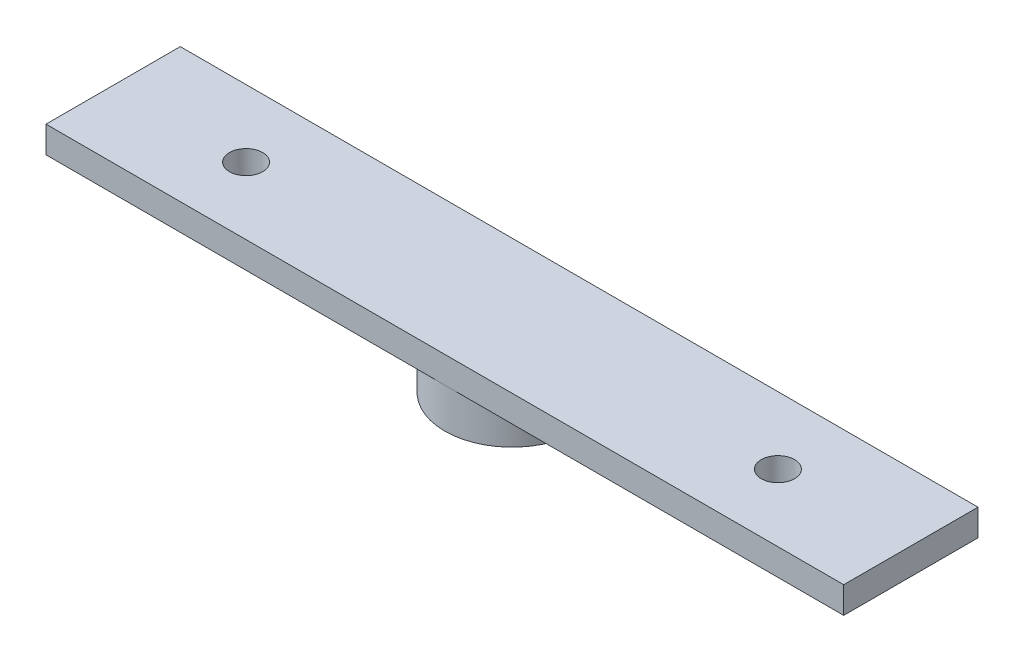
SolidWorks part; units mm, degrees
ref_plane "Front Plane" through (0, 0, 0) normal (0, 0, 1) x (1, 0, 0)
ref_plane "Top Plane" through (0, 0, 0) normal (0, 1, 0) x (1, 0, 0)
ref_plane "Right Plane" through (0, 0, 0) normal (1, 0, 0) x (0, 0, -1)
ref_axis "Axis1" through (0, 97.0223, 0) along (0, -1, 0)
sketch "Sketch1" plane through (0, 0, 0) normal (0, 0, 1) x (1, 0, 0)
  line L0 (3.05, 0) -> (3.05, 3)
  line L7 (5.05, 3) -> (5.05, 0)
  line L8 (5.05, 0) -> (3.05, 0)
  line L9 (3.05, 3) -> (5.05, 3)
  dimension "D1" = 3
  dimension "D2" = 5.05
  dimension "D3" = 3.05
revolve "Revolve1" add sketch "Sketch1" angle 360 about axis through (0, 97.0223, 0) along (0, -1, 0)
sketch "Sketch2" plane through (0, 3, 0) normal (0, 1, 0) x (1, 0, 0)
  line L1 (-30, -5.05) -> (30, -5.05)
  line L2 (-30, -5.05) -> (-30, 5.05)
  line L3 (-30, 5.05) -> (30, 5.05)
  line L4 (30, -5.05) -> (30, 5.05)
  line L5 (-30, -5.05) -> (30, 5.05) construction
  line L6 (-30, 5.05) -> (30, -5.05) construction
  circle A0 centre (0, 0) radius 5.05 construction
  point P0 (0, 0)
  dimension "D1" = 60
extrude "Boss-Extrude1" add sketch "Sketch2" along normal blind 2
sketch "Sketch3" plane through (0, 5, 0) normal (0, 1, 0) x (1, 0, 0)
  line L0 (-30, 5.05) -> (-30, -5.05) construction
  line L2 (0, -1.65) -> (0, 1.65) construction
  circle A6 centre (-20, 0) radius 1.25
  circle A7 centre (20, 0) radius 1.25
  point P9 (-30, 0)
  dimension "D1" = 2.5
  dimension "D2" = 10
extrude "Cut-Extrude1" cut sketch "Sketch3" against normal blind 5
